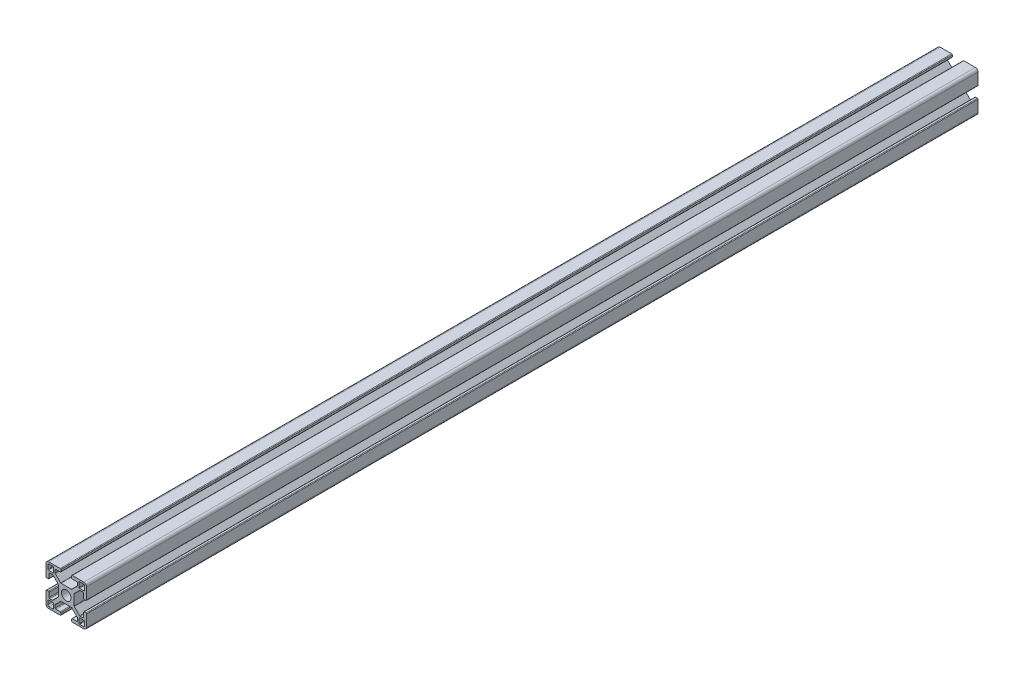
SolidWorks part; units mm, degrees
ref_plane "Front Plane" through (0, 0, 0) normal (0, 0, 1) x (1, 0, 0)
ref_plane "Top Plane" through (0, 0, 0) normal (0, 1, 0) x (1, 0, 0)
ref_plane "Right Plane" through (0, 0, 0) normal (1, 0, 0) x (0, 0, -1)
sketch "Sketch1" plane through (0, 0, 0) normal (0, 0, 1) x (1, 0, 0)
  line L0 (3.9799, -2.4733) -> (3.1981, -1.4942) construction
  line L1 (1.4942, -3.1981) -> (2.4733, -3.9799) construction
  line L2 (-2.4733, -3.9799) -> (-1.4942, -3.1981) construction
  line L3 (-3.1981, -1.4942) -> (-3.9799, -2.4733) construction
  line L4 (-3.9799, 2.4733) -> (-3.1981, 1.4942) construction
  line L5 (-1.4942, 3.1981) -> (-2.4733, 3.9799) construction
  line L6 (2.4733, 3.9799) -> (1.4942, 3.1981) construction
  line L7 (3.1981, 1.4942) -> (3.9799, 2.4733) construction
  line L8 (-12.6999, -13.6999) -> (-9.881, -13.6999)
  line L9 (-13.6999, -9.881) -> (-13.6999, -12.6999)
  line L10 (-9.88, -9.5) -> (-13.3189, -9.5)
  line L11 (-9.5, -13.3189) -> (-9.5, -9.88)
  line L12 (13.6999, -12.6999) -> (13.6999, -9.881)
  line L13 (9.881, -13.6999) -> (12.6999, -13.6999)
  line L14 (9.5, -9.88) -> (9.5, -13.3189)
  line L15 (13.3189, -9.5) -> (9.88, -9.5)
  line L16 (9.88, 9.5) -> (13.3189, 9.5)
  line L17 (9.5, 13.3189) -> (9.5, 9.88)
  line L18 (12.6999, 13.6999) -> (9.881, 13.6999)
  line L19 (13.6999, 9.881) -> (13.6999, 12.6999)
  line L20 (-13.6999, 12.6999) -> (-13.6999, 9.881)
  line L21 (-9.881, 13.6999) -> (-12.6999, 13.6999)
  line L22 (-9.5, 9.88) -> (-9.5, 13.3189)
  line L23 (-13.3189, 9.5) -> (-9.88, 9.5)
  line L24 (14.4999, -4) -> (13.2425, -4)
  line L25 (12.7425, -4.5) -> (12.7425, -7.7325)
  line L26 (12.2428, -8.25) -> (10.2602, -8.25)
  line L27 (9.9066, -8.1035) -> (5.9811, -4.178)
  line L28 (5.8347, -3.8245) -> (5.8347, -1.0125)
  line L29 (5.8347, -1.0125) -> (5.3247, -0.0625) construction
  line L30 (5.3247, -0.0625) -> (5.8347, 0.8875) construction
  line L31 (5.8347, 0.8875) -> (5.8347, 3.8245)
  line L32 (5.9811, 4.178) -> (9.9066, 8.1035)
  line L33 (10.2602, 8.25) -> (12.2428, 8.25)
  line L34 (12.7425, 7.7325) -> (12.7425, 4.5)
  line L35 (13.2425, 4) -> (14.4999, 4)
  line L36 (14.9999, 4.5) -> (14.9999, 12.9999)
  line L37 (12.9999, 14.9999) -> (4.5, 14.9999)
  line L38 (4, 14.4999) -> (4, 13.2425)
  line L39 (4.5, 12.7425) -> (7.7325, 12.7425)
  line L40 (8.25, 12.2428) -> (8.25, 10.2602)
  line L41 (8.1035, 9.9066) -> (4.178, 5.9811)
  line L42 (3.8245, 5.8347) -> (0.95, 5.8347)
  line L43 (0.95, 5.8347) -> (0, 5.3247) construction
  line L44 (0, 5.3247) -> (-0.95, 5.8347) construction
  line L45 (-0.95, 5.8347) -> (-3.8245, 5.8347)
  line L46 (-4.178, 5.9811) -> (-8.1035, 9.9066)
  line L47 (-8.25, 10.2602) -> (-8.25, 12.2428)
  line L48 (-7.7325, 12.7425) -> (-4.5, 12.7425)
  line L49 (-4, 13.2425) -> (-4, 14.4999)
  line L50 (-4.5, 14.9999) -> (-12.9999, 14.9999)
  line L51 (-14.9999, 12.9999) -> (-14.9999, 4.5)
  line L52 (-14.4999, 4) -> (-13.2425, 4)
  line L53 (-12.7425, 4.5) -> (-12.7425, 7.7325)
  line L54 (-12.2428, 8.25) -> (-10.2602, 8.25)
  line L55 (-9.9066, 8.1035) -> (-5.9811, 4.178)
  line L56 (-5.8347, 3.8245) -> (-5.8347, 0.8875)
  line L57 (-5.8347, 0.8875) -> (-5.3247, -0.0625) construction
  line L58 (-5.3247, -0.0625) -> (-5.8347, -1.0125) construction
  line L59 (-5.8347, -1.0125) -> (-5.8347, -3.8245)
  line L60 (-5.9811, -4.178) -> (-9.9066, -8.1035)
  line L61 (-10.2602, -8.25) -> (-12.2428, -8.25)
  line L62 (-12.7425, -7.7325) -> (-12.7425, -4.5)
  line L63 (-13.2425, -4) -> (-14.4999, -4)
  line L64 (-14.9999, -4.5) -> (-14.9999, -12.9999)
  line L65 (-12.9999, -14.9999) -> (-4.5, -14.9999)
  line L66 (-4, -14.4999) -> (-4, -13.2425)
  line L67 (-4.5, -12.7425) -> (-7.7325, -12.7425)
  line L68 (-8.25, -12.2428) -> (-8.25, -10.2602)
  line L69 (-8.1035, -9.9066) -> (-4.178, -5.9811)
  line L70 (-3.8245, -5.8347) -> (-0.95, -5.8347)
  line L71 (-0.95, -5.8347) -> (0, -5.3247) construction
  line L72 (0, -5.3247) -> (0.95, -5.8347) construction
  line L73 (0.95, -5.8347) -> (3.8245, -5.8347)
  line L74 (4.178, -5.9811) -> (8.1035, -9.9066)
  line L75 (8.25, -10.2602) -> (8.25, -12.2428)
  line L76 (7.7325, -12.7425) -> (4.5, -12.7425)
  line L77 (4, -13.2425) -> (4, -14.4999)
  line L78 (4.5, -14.9999) -> (12.9999, -14.9999)
  line L79 (14.9999, -12.9999) -> (14.9999, -4.5)
  line L80 (-5.8347, -1.0125) -> (-5.8347, 0.8875)
  line L81 (-0.95, 5.8347) -> (0.95, 5.8347)
  line L82 (5.8347, 0.8875) -> (5.8347, -1.0125)
  line L83 (-0.95, -5.8347) -> (0.95, -5.8347)
  arc A0 (2.4733, -3.9799) -> (3.9799, -2.4733) centre (3.1422, -3.1422) ccw construction
  arc A1 (-1.4942, -3.1981) -> (1.4942, -3.1981) centre (0, 0) ccw construction
  arc A2 (-3.9799, -2.4733) -> (-2.4733, -3.9799) centre (-3.1422, -3.1422) ccw construction
  arc A3 (-3.1981, 1.4942) -> (-3.1981, -1.4942) centre (0, 0) ccw construction
  arc A4 (-2.4733, 3.9799) -> (-3.9799, 2.4733) centre (-3.1422, 3.1422) ccw construction
  arc A5 (1.4942, 3.1981) -> (-1.4942, 3.1981) centre (0, 0) ccw construction
  arc A6 (3.9799, 2.4733) -> (2.4733, 3.9799) centre (3.1422, 3.1422) ccw construction
  arc A7 (3.1981, -1.4942) -> (3.1981, 1.4942) centre (0, 0) ccw construction
  arc A8 (-13.6999, -12.6999) -> (-12.6999, -13.6999) centre (-12.6999, -12.6999) ccw
  arc A9 (-13.3189, -9.5) -> (-13.6999, -9.881) centre (-13.3189, -9.881) ccw
  arc A10 (-9.5, -9.88) -> (-9.88, -9.5) centre (-9.88, -9.88) ccw
  arc A11 (-9.881, -13.6999) -> (-9.5, -13.3189) centre (-9.881, -13.3189) ccw
  arc A12 (12.6999, -13.6999) -> (13.6999, -12.6999) centre (12.6999, -12.6999) ccw
  arc A13 (9.5, -13.3189) -> (9.881, -13.6999) centre (9.881, -13.3189) ccw
  arc A14 (9.88, -9.5) -> (9.5, -9.88) centre (9.88, -9.88) ccw
  arc A15 (13.6999, -9.881) -> (13.3189, -9.5) centre (13.3189, -9.881) ccw
  arc A16 (9.5, 9.88) -> (9.88, 9.5) centre (9.88, 9.88) ccw
  arc A17 (9.881, 13.6999) -> (9.5, 13.3189) centre (9.881, 13.3189) ccw
  arc A18 (13.6999, 12.6999) -> (12.6999, 13.6999) centre (12.6999, 12.6999) ccw
  arc A19 (13.3189, 9.5) -> (13.6999, 9.881) centre (13.3189, 9.881) ccw
  arc A20 (14.9999, -4.5) -> (14.4999, -4) centre (14.4999, -4.5) ccw
  arc A21 (13.2425, -4) -> (12.7425, -4.5) centre (13.2425, -4.5) ccw
  arc A22 (12.2428, -8.25) -> (12.7425, -7.7325) centre (12.2428, -7.75) ccw
  arc A23 (9.9066, -8.1035) -> (10.2602, -8.25) centre (10.2602, -7.75) ccw
  arc A24 (5.8347, -3.8245) -> (5.9811, -4.178) centre (6.3347, -3.8245) ccw
  arc A25 (5.9811, 4.178) -> (5.8347, 3.8245) centre (6.3347, 3.8245) ccw
  arc A26 (10.2602, 8.25) -> (9.9066, 8.1035) centre (10.2602, 7.75) ccw
  arc A27 (12.7425, 7.7325) -> (12.2428, 8.25) centre (12.2428, 7.75) ccw
  arc A28 (12.7425, 4.5) -> (13.2425, 4) centre (13.2425, 4.5) ccw
  arc A29 (14.4999, 4) -> (14.9999, 4.5) centre (14.4999, 4.5) ccw
  arc A30 (14.9999, 12.9999) -> (12.9999, 14.9999) centre (12.9999, 12.9999) ccw
  arc A31 (4.5, 14.9999) -> (4, 14.4999) centre (4.5, 14.4999) ccw
  arc A32 (4, 13.2425) -> (4.5, 12.7425) centre (4.5, 13.2425) ccw
  arc A33 (8.25, 12.2428) -> (7.7325, 12.7425) centre (7.75, 12.2428) ccw
  arc A34 (8.1035, 9.9066) -> (8.25, 10.2602) centre (7.75, 10.2602) ccw
  arc A35 (3.8245, 5.8347) -> (4.178, 5.9811) centre (3.8245, 6.3347) ccw
  arc A36 (-4.178, 5.9811) -> (-3.8245, 5.8347) centre (-3.8245, 6.3347) ccw
  arc A37 (-8.25, 10.2602) -> (-8.1035, 9.9066) centre (-7.75, 10.2602) ccw
  arc A38 (-7.7325, 12.7425) -> (-8.25, 12.2428) centre (-7.75, 12.2428) ccw
  arc A39 (-4.5, 12.7425) -> (-4, 13.2425) centre (-4.5, 13.2425) ccw
  arc A40 (-4, 14.4999) -> (-4.5, 14.9999) centre (-4.5, 14.4999) ccw
  arc A41 (-12.9999, 14.9999) -> (-14.9999, 12.9999) centre (-12.9999, 12.9999) ccw
  arc A42 (-14.9999, 4.5) -> (-14.4999, 4) centre (-14.4999, 4.5) ccw
  arc A43 (-13.2425, 4) -> (-12.7425, 4.5) centre (-13.2425, 4.5) ccw
  arc A44 (-12.2428, 8.25) -> (-12.7425, 7.7325) centre (-12.2428, 7.75) ccw
  arc A45 (-9.9066, 8.1035) -> (-10.2602, 8.25) centre (-10.2602, 7.75) ccw
  arc A46 (-5.8347, 3.8245) -> (-5.9811, 4.178) centre (-6.3347, 3.8245) ccw
  arc A47 (-5.9811, -4.178) -> (-5.8347, -3.8245) centre (-6.3347, -3.8245) ccw
  arc A48 (-10.2602, -8.25) -> (-9.9066, -8.1035) centre (-10.2602, -7.75) ccw
  arc A49 (-12.7425, -7.7325) -> (-12.2428, -8.25) centre (-12.2428, -7.75) ccw
  arc A50 (-12.7425, -4.5) -> (-13.2425, -4) centre (-13.2425, -4.5) ccw
  arc A51 (-14.4999, -4) -> (-14.9999, -4.5) centre (-14.4999, -4.5) ccw
  arc A52 (-14.9999, -12.9999) -> (-12.9999, -14.9999) centre (-12.9999, -12.9999) ccw
  arc A53 (-4.5, -14.9999) -> (-4, -14.4999) centre (-4.5, -14.4999) ccw
  arc A54 (-4, -13.2425) -> (-4.5, -12.7425) centre (-4.5, -13.2425) ccw
  arc A55 (-8.25, -12.2428) -> (-7.7325, -12.7425) centre (-7.75, -12.2428) ccw
  arc A56 (-8.1035, -9.9066) -> (-8.25, -10.2602) centre (-7.75, -10.2602) ccw
  arc A57 (-3.8245, -5.8347) -> (-4.178, -5.9811) centre (-3.8245, -6.3347) ccw
  arc A58 (4.178, -5.9811) -> (3.8245, -5.8347) centre (3.8245, -6.3347) ccw
  arc A59 (8.25, -10.2602) -> (8.1035, -9.9066) centre (7.75, -10.2602) ccw
  arc A60 (7.7325, -12.7425) -> (8.25, -12.2428) centre (7.75, -12.2428) ccw
  arc A61 (4.5, -12.7425) -> (4, -13.2425) centre (4.5, -13.2425) ccw
  arc A62 (4, -14.4999) -> (4.5, -14.9999) centre (4.5, -14.4999) ccw
  arc A63 (12.9999, -14.9999) -> (14.9999, -12.9999) centre (12.9999, -12.9999) ccw
  arc A64 (-12.6999, 13.6999) -> (-13.6999, 12.6999) centre (-12.6999, 12.6999) ccw
  arc A65 (-9.5, 13.3189) -> (-9.881, 13.6999) centre (-9.881, 13.3189) ccw
  arc A66 (-9.88, 9.5) -> (-9.5, 9.88) centre (-9.88, 9.88) ccw
  arc A67 (-13.6999, 9.881) -> (-13.3189, 9.5) centre (-13.3189, 9.881) ccw
  circle A68 centre (0, 0) radius 3.53
extrude "Boss-Extrude1" add sketch "Sketch1" along normal mid plane 660.4
